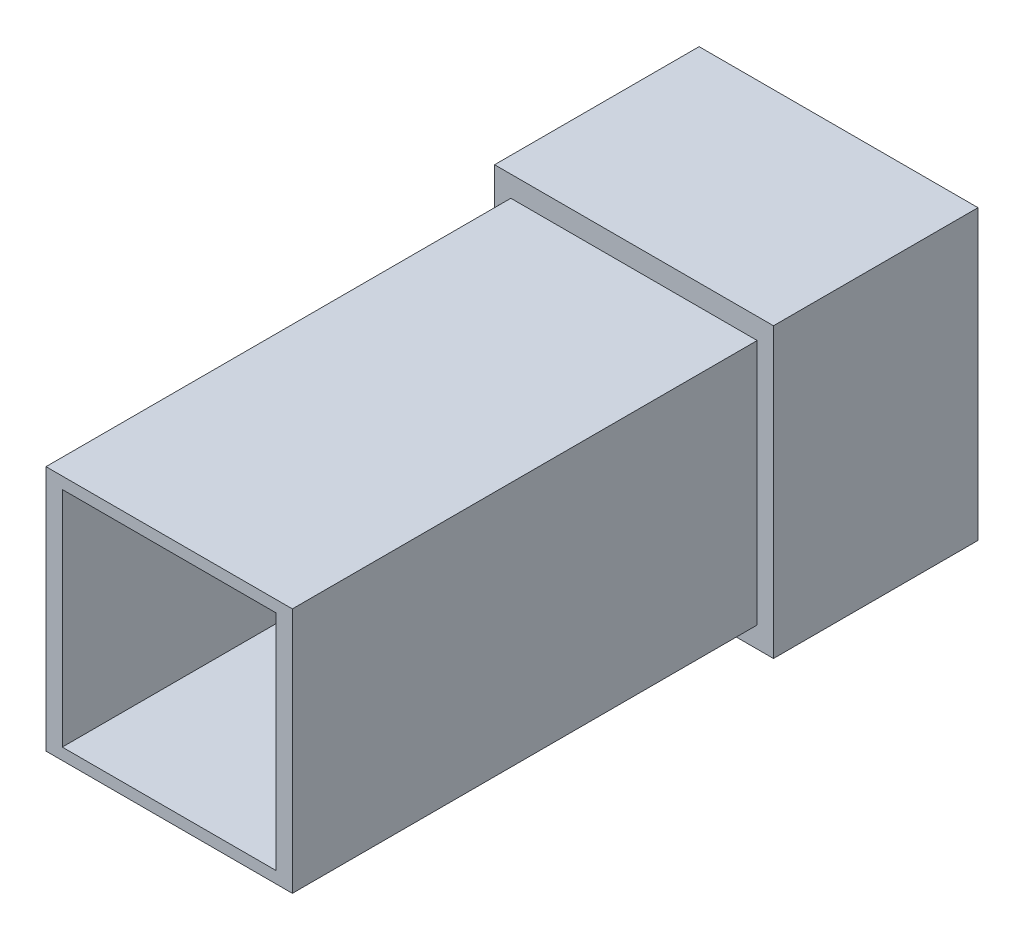
SolidWorks part; units mm, degrees
ref_plane "Front Plane" through (0, 0, 0) normal (0, 0, 1) x (1, 0, 0)
ref_plane "Top Plane" through (0, 0, 0) normal (0, 1, 0) x (1, 0, 0)
ref_plane "Right Plane" through (0, 0, 0) normal (1, 0, 0) x (0, 0, -1)
sketch "Sketch1" plane through (0, 0, 0) normal (0, 0, 1) x (1, 0, 0)
  line L1 (0, 0) -> (68.58, 0)
  line L2 (0, 0) -> (0, 71.12)
  line L3 (0, 71.12) -> (68.58, 71.12)
  line L4 (68.58, 0) -> (68.58, 71.12)
  line L5 (2.54, 68.58) -> (66.04, 68.58)
  line L6 (2.54, 68.58) -> (2.54, 2.54)
  line L7 (2.54, 2.54) -> (66.04, 2.54)
  line L8 (66.04, 68.58) -> (66.04, 2.54)
  line L9 (-3.81, 74.93) -> (72.39, 74.93)
  line L10 (-3.81, 74.93) -> (-3.81, -3.81)
  line L11 (-3.81, -3.81) -> (72.39, -3.81)
  line L12 (72.39, 74.93) -> (72.39, -3.81)
  line L13 (5.08, 66.04) -> (63.5, 66.04)
  line L14 (5.08, 66.04) -> (5.08, 5.08)
  line L15 (5.08, 5.08) -> (63.5, 5.08)
  line L16 (63.5, 66.04) -> (63.5, 5.08)
  point P9 (34.29, 71.12)
  point P10 (34.29, 68.58)
  point P11 (66.04, 35.56)
  point P12 (68.58, 35.56)
  dimension "D1" = 68.58
  dimension "D2" = 71.12
  dimension "D3" = 66.04
  dimension "D4" = 63.5
  dimension "D5" = 3.81
  dimension "D6" = 3.81
  dimension "D7" = 3.81
  dimension "D8" = 3.81
  dimension "D9" = 2.54
  dimension "D10" = 2.54
  dimension "D11" = 2.54
  dimension "D12" = 2.54
extrude "Boss-Extrude1" add sketch "Sketch1" along normal blind 50.8 contours L12 L9 L10 L11 L4 L1 L2 L3 | L8 L5 L6 L7 L13 L16 L15 L14
sketch "Sketch2" plane through (0, 0, 50.8) normal (0, 0, 1) x (1, 0, 0)
  line L1 (-3.81, 74.93) -> (72.39, 74.93)
  line L2 (-3.81, 74.93) -> (-3.81, -3.81)
  line L3 (-3.81, -3.81) -> (72.39, -3.81)
  line L4 (72.39, 74.93) -> (72.39, -3.81)
  line L5 (63.5, 5.08) -> (5.08, 5.08)
  line L6 (63.5, 5.08) -> (63.5, 66.04)
  line L7 (63.5, 66.04) -> (5.08, 66.04)
  line L8 (5.08, 5.08) -> (5.08, 66.04)
extrude "Boss-Extrude2" add sketch "Sketch2" along normal blind 5.08
sketch "Sketch3" plane through (0, 0, 55.88) normal (0, 0, 1) x (1, 0, 0)
  line L1 (5.08, 66.04) -> (63.5, 66.04)
  line L2 (5.08, 66.04) -> (5.08, 5.08)
  line L3 (5.08, 5.08) -> (63.5, 5.08)
  line L4 (63.5, 66.04) -> (63.5, 5.08)
  line L5 (0.635, 69.215) -> (67.945, 69.215)
  line L6 (0.635, 69.215) -> (0.635, 1.905)
  line L7 (0.635, 1.905) -> (67.945, 1.905)
  line L8 (67.945, 69.215) -> (67.945, 1.905)
  point P10 (34.29, 69.215)
  point P11 (34.29, 66.04)
  point P12 (0.635, 35.56)
  point P13 (5.08, 35.56)
  point P14 (0, 0)
  point P15 (0, 0)
  dimension "D1" = 67.31
extrude "Boss-Extrude3" add sketch "Sketch3" along normal blind 127
